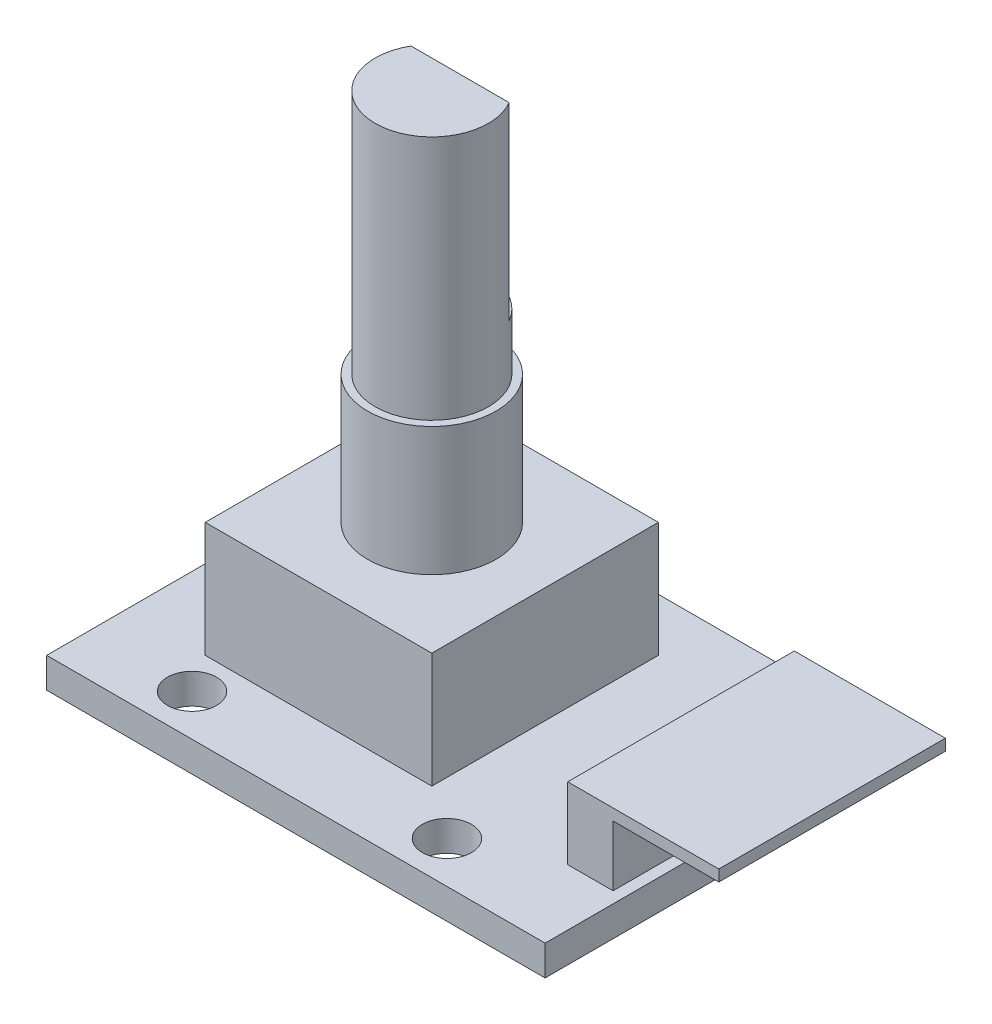
SolidWorks part; units mm, degrees
ref_plane "Front Plane" through (0, 0, 0) normal (0, 0, 1) x (1, 0, 0)
ref_plane "Top Plane" through (0, 0, 0) normal (0, 1, 0) x (1, 0, 0)
ref_plane "Right Plane" through (0, 0, 0) normal (1, 0, 0) x (0, 0, -1)
sketch "Sketch2" plane through (0, 0, 0) normal (0, 1, 0) x (1, 0, 0)
  line L1 (0, 0) -> (26.4, 0)
  line L2 (0, 0) -> (0, 19)
  line L3 (0, 19) -> (26.4, 19)
  line L4 (26.4, 0) -> (26.4, 19)
  dimension "D1" = 26.4
  dimension "D2" = 19
extrude "Boss-Extrude1" add sketch "Sketch2" along normal blind 1.6
sketch "Sketch3" plane through (0, 1.6, 0) normal (0, 1, 0) x (1, 0, 0)
  line L0 (5.5, 2.2) -> (19, 2.2) construction
  line L1 (0, 19) -> (0, 0) construction
  line L2 (0, 0) -> (26.4, 0) construction
  circle A0 centre (5.5, 2.2) radius 1.3
  circle A1 centre (19, 2.2) radius 1.3
  dimension "D3" = 2.6
  dimension "D1" = 5.5
  dimension "D2" = 19
  dimension "D4" = 2.2
extrude "Cut-Extrude1" cut sketch "Sketch3" against normal through all
sketch "Sketch4" plane through (0, 1.6, 0) normal (0, 1, 0) x (1, 0, 0)
  line L0 (0, 0) -> (26.4, 0) construction
  line L1 (4.2, 16.2) -> (16.2, 16.2)
  line L2 (4.2, 16.2) -> (4.2, 4.2)
  line L3 (4.2, 4.2) -> (16.2, 4.2)
  line L4 (16.2, 16.2) -> (16.2, 4.2)
  line L5 (0, 19) -> (0, 0) construction
  dimension "D1" = 12
  dimension "D2" = 4.2
  dimension "D3" = 4.2
extrude "Boss-Extrude2" add sketch "Sketch4" along normal blind 6.1
sketch "Sketch5" plane through (0, 7.7, 0) normal (0, 1, 0) x (1, 0, 0)
  line L0 (4.2, 4.2) -> (16.2, 16.2) construction
  circle A0 centre (10.2, 10.2) radius 3.4
  dimension "D1" = 6.8
extrude "Boss-Extrude3" add sketch "Sketch5" along normal blind 6.8
sketch "Sketch6" plane through (0, 14.5, 0) normal (0, 1, 0) x (1, 0, 0)
  circle A0 centre (10.2, 10.2) radius 3
  dimension "D1" = 6
extrude "Boss-Extrude4" add sketch "Sketch6" along normal blind 3
sketch "Sketch7" plane through (0, 17.5, 0) normal (0, 1, 0) x (1, 0, 0)
  line L1 (7.6019, 11.7) -> (12.7981, 11.7)
  line L2 (7.6019, 11.7) -> (7.6019, 7.2)
  line L3 (7.6019, 7.2) -> (12.7981, 7.2)
  line L4 (12.7981, 11.7) -> (12.7981, 7.2)
  circle A0 centre (10.2, 10.2) radius 3
  circle A1 centre (10.2, 10.2) radius 3 construction
  point P7 (0, 0)
  point P8 (0, 0)
  circle M6 centre (10.2, 10.2) radius 3
  dimension "D1" = 4.5
extrude "Boss-Extrude5" add sketch "Sketch7" along normal blind 10 contours L4 M6 | L2 M6 | L4 L1 L2 M6
sketch "Sketch8" plane through (0, 1.6, 0) normal (0, 1, 0) x (1, 0, 0)
  line L0 (26.4, 0) -> (26.4, 19) construction
  line L1 (26.4, 16.2) -> (31.4, 16.2)
  line L2 (26.4, 16.2) -> (26.4, 4.2)
  line L3 (26.4, 4.2) -> (31.4, 4.2)
  line L4 (31.4, 16.2) -> (31.4, 4.2)
  line L5 (4.2, 4.2) -> (16.2, 4.2) construction
  line L7 (16.2, 4.2) -> (16.2, 16.2) construction
  line L9 (26.4, 16.2) -> (23.4, 16.2)
  line L10 (26.4, 16.2) -> (26.4, 4.2)
  line L11 (26.4, 4.2) -> (23.4, 4.2)
  line L12 (23.4, 16.2) -> (23.4, 4.2)
  line M8 (26.4, 0) -> (26.4, 19)
  dimension "D1" = 5
  dimension "D2" = 8
extrude "Boss-Extrude6" add sketch "Sketch8" along normal blind 3.8 contours L9 L12 L11 M8 | L4 L1 L3 M8
sketch "Sketch9" plane through (0, 0, -4.2) normal (0, 0, 1) x (1, 0, 0)
  line L0 (31.4, 5.4) -> (23.4, 5.4) construction
  line L1 (31.4, 1.6) -> (25.8, 1.6)
  line L2 (31.4, 1.6) -> (31.4, 4.8)
  line L3 (31.4, 4.8) -> (25.8, 4.8)
  line L4 (25.8, 1.6) -> (25.8, 4.8)
  dimension "D1" = 5.6
  dimension "D2" = 0.6
extrude "Cut-Extrude2" cut sketch "Sketch9" against normal through all
